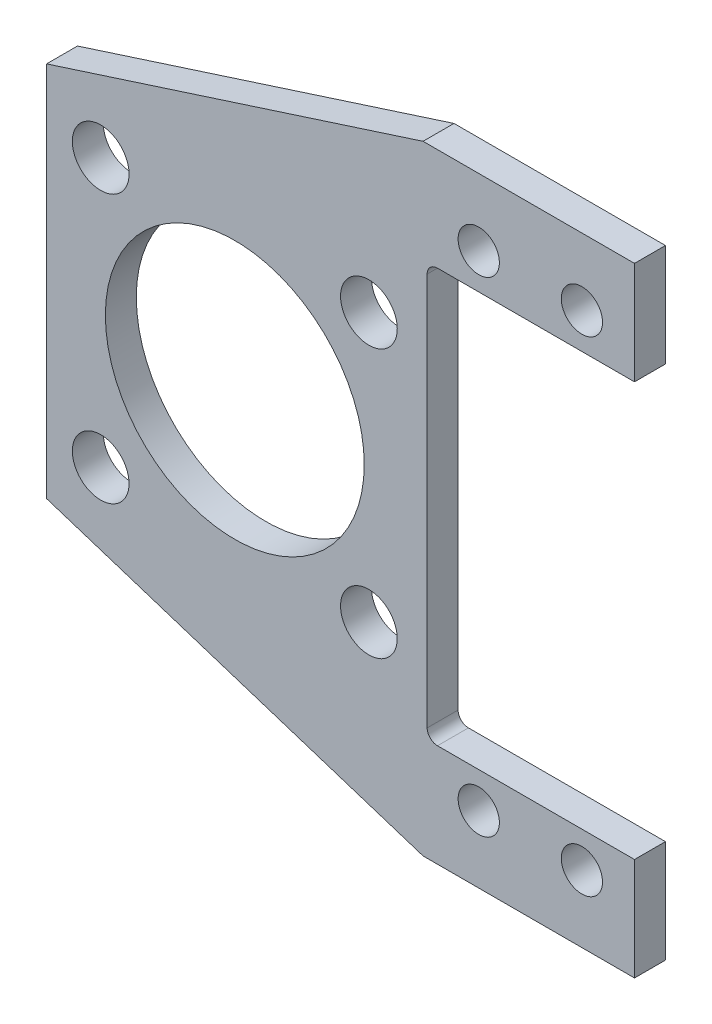
SolidWorks part; units mm, degrees
ref_plane "Front Plane" through (0, 0, 0) normal (1, 0, 0) x (0, 1, 0)
ref_plane "Top Plane" through (0, 0, 0) normal (0, 0, 1) x (0, 1, 0)
ref_plane "Right Plane" through (0, 0, 0) normal (0, 1, 0) x (-1, 0, 0)
sketch "Sketch1" plane through (0, 0, 0) normal (0, 0, 1) x (0, 1, 0)
  line L0 (0, 0) -> (0, -51.214) construction
  line L3 (-18.25, 18.25) -> (18.25, 18.25)
  line L5 (-18.25, -18.25) -> (18.25, 18.25) construction
  line L6 (-18.25, 18.25) -> (18.25, -18.25) construction
  line L7 (-30, -38.75) -> (-20.05, -38.75)
  line L8 (-30, -38.75) -> (-30, -18.25)
  line L10 (30, -38.75) -> (30, -18.25)
  line L11 (-30, -38.75) -> (30, -18.25) construction
  line L12 (-20.05, -21.6496) -> (30, -38.75) construction
  line L14 (-20.05, -38.75) -> (-20.05, -19.65)
  line L15 (-19.05, -18.65) -> (19.05, -18.65)
  line L16 (20.05, -38.75) -> (20.05, -19.65)
  line L17 (-20.05, -38.75) -> (20.05, -18.65) construction
  line L18 (-20.05, -18.65) -> (20.05, -38.75) construction
  line L19 (20.05, -38.75) -> (30, -38.75)
  line L21 (-18.25, 18.25) -> (-30, -18.25)
  line L22 (18.25, 18.25) -> (30, -18.25)
  line L23 (0, 0) -> (-19.05, 0) construction
  line L24 (0, 0) -> (0, 15.5965) construction
  arc A0 (19.05, -18.65) -> (20.05, -19.65) centre (19.05, -19.65) cw
  arc A1 (-20.05, -19.65) -> (-19.05, -18.65) centre (-19.05, -19.65) cw
  circle A2 centre (-13, 13) radius 2.75
  circle A3 centre (0, 0) radius 12.55
  circle A4 centre (13, 13) radius 2.75
  circle A5 centre (13, -13) radius 2.75
  circle A6 centre (-13, -13) radius 2.75
  circle A7 centre (-23.5, -23.65) radius 2
  circle A8 centre (23.5, -23.65) radius 2
  circle A9 centre (23.5, -33.65) radius 2
  circle A10 centre (-23.5, -33.65) radius 2
  point P0 (0, 0)
  point P6 (0, -28.5)
  point P11 (0, -28.7)
  dimension "D7" = 1
  dimension "D9" = 5.5
  dimension "D12" = 25.1
  dimension "D15" = 4
  dimension "D1" = 36.5
  dimension "D2" = 36.5
  dimension "D3" = 9.95
  dimension "D4" = 20.5
  dimension "D5" = 40.1
  dimension "D6" = 20.1
  dimension "D8" = 9.95
  dimension "D10" = 13
  dimension "D11" = 13
  dimension "D16" = 3.45
  dimension "D19" = 5
  dimension "D13" = 2
  dimension "D14" = 2
  dimension "D17" = 2
  dimension "D18" = 2
extrude "Boss-Extrude1" add sketch "Sketch1" along normal blind 3
